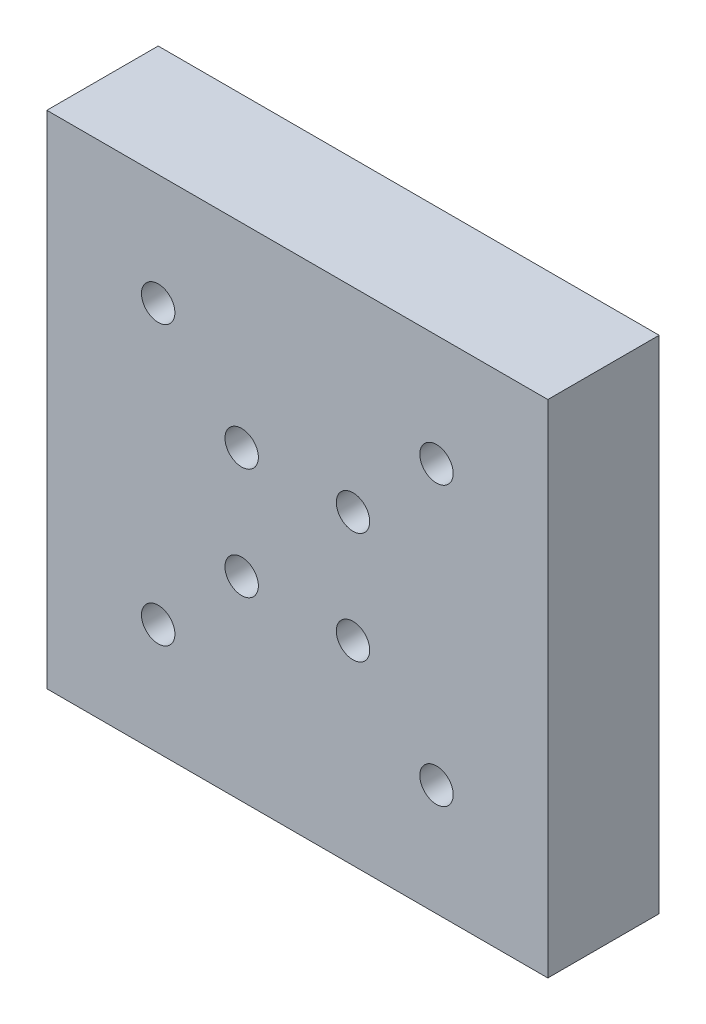
SolidWorks part; units mm, degrees
ref_plane "Front Plane" through (0, 0, 0) normal (0, 0, 1) x (1, 0, 0)
ref_plane "Top Plane" through (0, 0, 0) normal (0, 1, 0) x (1, 0, 0)
ref_plane "Right Plane" through (0, 0, 0) normal (1, 0, 0) x (0, 0, -1)
sketch "Sketch1" plane through (0, 0, 0) normal (0, 0, 1) x (1, 0, 0)
  line L1 (-22.5, 22.5) -> (22.5, 22.5)
  line L2 (-22.5, 22.5) -> (-22.5, -22.5)
  line L3 (-22.5, -22.5) -> (22.5, -22.5)
  line L4 (22.5, 22.5) -> (22.5, -22.5)
  line L5 (-22.5, 22.5) -> (22.5, -22.5) construction
  line L6 (-22.5, -22.5) -> (22.5, 22.5) construction
  point P0 (0, 0)
  dimension "D1" = 45
  dimension "D2" = 45
extrude "Boss-Extrude1" add sketch "Sketch1" along normal blind 10
sketch "Sketch2" plane through (0, 0, 10) normal (0, 0, 1) x (1, 0, 0)
  line L0 (-22.1542, 0) -> (24.4523, 0) construction
  line L1 (0, 24.9855) -> (0, -27.1035) construction
  circle A0 centre (-12.5, 12.5) radius 1.5
  circle A1 centre (12.5, 12.5) radius 1.5
  circle A2 centre (12.5, -12.5) radius 1.5
  circle A3 centre (-12.5, -12.5) radius 1.5
  dimension "D7" = 3
  dimension "D8" = 3
  dimension "D9" = 3
  dimension "D10" = 3
  dimension "D1" = 25
  dimension "D2" = 25
  dimension "D3" = 25
  dimension "D4" = 25
  dimension "D5" = 12.5
  dimension "D6" = 12.5
  dimension "D11" = 12.5
  dimension "D12" = 12.5
extrude "Cut-Extrude1" cut sketch "Sketch2" against normal blind 10
sketch "Sketch3" plane through (0, 0, 10) normal (0, 0, 1) x (1, 0, 0)
  line L0 (-21.097, 0) -> (20.1515, 0) construction
  line L1 (0, 19.7674) -> (0, -19.0583) construction
  line L2 (-12.5, 12.5) -> (12.5, -12.5) construction
  line L3 (-12.5, -12.5) -> (12.5, 12.5) construction
  circle A0 centre (-5, 5) radius 1.5
  circle A1 centre (5, 5) radius 1.5
  circle A2 centre (5, -5) radius 1.5
  circle A3 centre (-5, -5) radius 1.5
  dimension "D6" = 3
  dimension "D7" = 3
  dimension "D8" = 3
  dimension "D9" = 3
  dimension "D1" = 5
  dimension "D2" = 5
  dimension "D3" = 10
  dimension "D4" = 10
  dimension "D5" = 10
extrude "Cut-Extrude2" cut sketch "Sketch3" against normal blind 10
